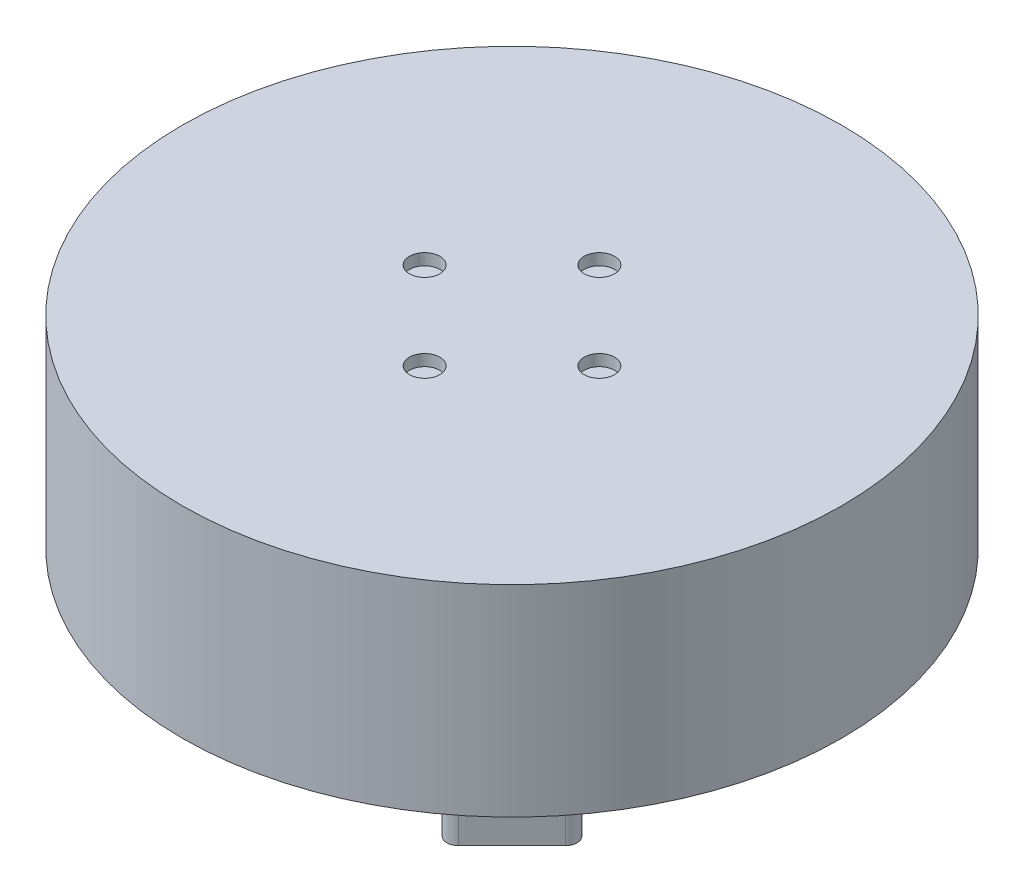
SolidWorks part; units mm, degrees
ref_plane "Front Plane" through (0, 0, 0) normal (0, 0, 1) x (1, 0, 0)
ref_plane "Top Plane" through (0, 0, 0) normal (0, 1, 0) x (1, 0, 0)
ref_plane "Right Plane" through (0, 0, 0) normal (1, 0, 0) x (0, 0, -1)
sketch "Sketch1" plane through (0, 0, 0) normal (0, 1, 0) x (1, 0, 0)
  circle A0 centre (0, 0) radius 43.4
  dimension "D1" = 86.8
extrude "Boss-Extrude1" add sketch "Sketch1" along normal blind 26.5
sketch "Sketch2" plane through (0, 0, 0) normal (0, -1, 0) x (1, 0, 0)
  circle A0 centre (0, 0) radius 16 construction
  circle A1 centre (0, 16) radius 2
  circle A2 centre (16, 0) radius 2
  circle A3 centre (0, -16) radius 2
  circle A4 centre (-16, 0) radius 2
  point P14 (0, 0)
  dimension "D1" = 32
  dimension "D2" = 4
  dimension "D3" = 4
extrude "Cut-Extrude1" cut sketch "Sketch2" against normal blind 1.5
sketch "Sketch3" plane through (0, 0, 0) normal (0, -1, 0) x (1, 0, 0)
  line L0 (0, 0) -> (0, 16) construction
  line L1 (0, 16) -> (16, 0) construction
  line L2 (16, 0) -> (0, 0) construction
  line L3 (0, 0) -> (26.8701, 26.8701) construction
  line L4 (23.3345, 30.4056) -> (30.4056, 23.3345) construction
  line L5 (25.1023, 32.1734) -> (32.1734, 25.1023) construction
  line L6 (21.5668, 28.6378) -> (28.6378, 21.5668) construction
  line L7 (24.3952, 31.4663) -> (31.4663, 24.3952)
  line L8 (22.2739, 29.3449) -> (29.3449, 22.2739)
  arc A0 (25.1023, 32.1734) -> (21.5668, 28.6378) centre (23.3345, 30.4056) ccw construction
  arc A1 (28.6378, 21.5668) -> (32.1734, 25.1023) centre (30.4056, 23.3345) ccw construction
  arc A2 (29.3449, 22.2739) -> (31.4663, 24.3952) centre (30.4056, 23.3345) ccw
  arc A3 (24.3952, 31.4663) -> (22.2739, 29.3449) centre (23.3345, 30.4056) ccw
  point P9 (26.8701, 26.8701)
  dimension "D3" = 2.5
  dimension "D1" = 38
  dimension "D2" = 10
  dimension "D4" = 1
extrude "Boss-Extrude2" add sketch "Sketch3" along normal blind 6
sketch "Sketch4" plane through (0, 26.5, 0) normal (0, 1, 0) x (1, 0, 0)
  circle A0 centre (0, 0) radius 11.5 construction
  circle A1 centre (0, 11.5) radius 2
  circle A2 centre (11.5, 0) radius 2
  circle A3 centre (0, -11.5) radius 2
  circle A4 centre (-11.5, 0) radius 2
  point P14 (0, 0)
  dimension "D2" = 4
  dimension "D3" = 4
  dimension "D1" = 23
extrude "Cut-Extrude2" cut sketch "Sketch4" against normal blind 1.5
equation "\"Np_b\" = 48"
equation "\"module\" = 0.5"
equation "\"pressure angle\" = 20.0"
equation "\"h_a\" = 0.5"
equation "\"h_b\" = 0.625"
equation "\"clr_tip_root\" = 0.125"
equation "\"fw_p_s\" = 15.90536252346366"
equation "\"Nr_s\" = 132"
equation "\"pressure_angle\" = 20.0"
equation "\"h_f\" = 0.625"
equation "\"dp_r_s\" = 66.0"
equation "\"db_r_s\" = 62.01971297186996"
equation "\"fw_r_s\" = 14.40536252346366"
equation "\"alpha_r_s\" = 0.8539582918412449"
equation "\"beta_r_s\" = 3.071552947318853"
equation "\"bearing_ID\" = 60"
equation "\"bearing_OD\" = 78"
equation "\"bearing_height\" = 10"
equation "\"clearance_planet\" = 1.5"
equation "\"case_dist\" = 6.5"
equation "\"Motor_case_OD_max\" = 111.3"
equation "\"case_mounting_PCD\" = 103.8"
equation "\"bearing mount thickness\" = 8"
equation "\"case_mounting_hole_dia\" = 3"
equation "\"output_mounting_PCD\" = 86"
equation "\"output_mounting_hole_dia\" = 4"
equation "\"clearance_case_mount_holes_shell_thickness\" = 1"
equation "\"motor_case_OD_base\" = 101.8"
equation "\"sec_carrier_thickness\" = 5"
equation "\"sun_coupler_hub_thickness\" = 4"
equation "\"clearance_sun_coupler_sec_carrier\" = 1.5"
equation "\"clearance_motor_and_case\" = 5"
equation "\"motor_OD\" = 86.8"
equation "\"Motor_case_thickness\" = 2.5"
equation "\"Motor_case_ID\" = 96.8"
equation "\"case_mounting_hole_shift\" = 1.0"
equation "\"output_mounting_nut_wrench_size\" = 7"
equation "\"output_mounting_nut_thickness\" = 3.2"
equation "\"case_mounting_hole_allen_socket_dia\" = 5.5"
equation "\"output_mounting_nut_depth\" = 3"
equation "\"case_mounting_bolt_depth\" = 4.5"
equation "\"Ns\" = 56"
equation "\"ring_radial_thickness\" = 5"
equation "\"ring_OD\"= \"Nr_s\" * \"module\" + \"ring_radial_thickness\" * 2"
equation "\"ring_to_chamfer_clearance\" = 1.5"
equation "\"Motor_case_OD_base_to_chamfer\" = 5"
equation "\"pattern_offset_from_motor_case_OD_base\" = 3"
equation "\"pattern_bulge_dia\" = 3"
equation "\"pattern_num_bulge\" = 18"
equation "\"pattern_depth\" = 2"
equation "\"motor_height\" = 26.5"
equation "\"case_mounting_wrench_size\" = 5.5"
equation "\"case_mounting_nut_clearance\" = 2"
equation "\"base_plate_thickness\" = 4"
equation "\"case_mounting_nut_thickness\" = 2.4"
equation "\"case_mounting_surface_height\" = 4"
equation "\"motor_mount_hole_PCD\" = 32"
equation "\"motor_mount_hole_dia\" = 4"
equation "\"motor_mount_hole_num\" = 4"
equation "\"central_hole_offset_from_motor_mount_PCD\" = 5"
equation "\"wire_slot_dist_from_center\" = 38"
equation "\"wire_slot_length\" = 10"
equation "\"wire_slot_radius\" = 2.5"
equation "\"driver_upper_holes_dist_from_center\" = 29"
equation "\"driver_lower_holes_dist_from_center\" = 13"
equation "\"driver_side_holes_dist_from_center\" = 22.5"
equation "\"driver_mount_holes_dia\" = 3"
equation "\"driver_mount_inserts_OD\" = 4.8"
equation "\"driver_mount_thickness\" = 1.5"
equation "\"driver_mount_height\" = 6"
equation "\"air_flow_hole_offset\" = 3"
equation "\"num_planet\" = 4"
equation "\"planet_pin_bolt_dia\" = 5"
equation "\"planet_pin_socket_head_dia\" = 8.5"
equation "\"carrier_PCD\" = 52.0"
equation "\"planet_shaft_dia\" = 8"
equation "\"planet_shaft_step_offset\" = 1"
equation "\"carrier_trapezoidal_support_sun_offset\" = 5"
equation "\"carrier_trapezoidal_support_hole_PCD_offset_bearing_ID\" = 4"
equation "\"carrier_trapezoidal_support_hole_dia\" = 3"
equation "\"carrier_trapezoidal_support_hole_socket_head_dia\" = 5.5"
equation "\"carrier_bearing_step_width\" = 1.5"
equation "\"standard_clearance_1_5mm\" = 1.5"
equation "\"standard_fillet_1_5mm\" = 1.5"
equation "\"sun_shaft_bearing_OD\" = 16"
equation "\"sun_shaft_bearing_width\" = 5"
equation "\"standard_bearing_insertion_chamfer\" = 0.5"
equation "\"carrier_trapezoidal_support_hole_wrench_size\" = 5.5"
equation "\"planet_pin_bolt_wrench_size\" = 8"
equation "\"planet_bearing_OD\" = 12"
equation "\"planet_bearing_width\" = 3.5"
equation "\"planet_bore\" = 10"
equation "\"D1@Boss-Extrude1\"=\"motor_height\""
equation "\"D1@Sketch1\"=\"motor_OD\""
equation "\"D1@Sketch2\"=\"motor_mount_hole_PCD\""
equation "\"D2@Sketch2\"=\"motor_mount_hole_dia\""
equation "\"D3@Sketch2\"=\"motor_mount_hole_num\""
equation "\"D1@Cut-Extrude1\"=\"standard_clearance_1_5mm\""
equation "\"D1@Sketch3\"=\"wire_slot_dist_from_center\""
equation "\"D2@Sketch3\"=\"wire_slot_length\""
equation "\"D3@Sketch3\"=\"wire_slot_radius\""
equation "\"D1@Boss-Extrude2\"=\"standard_clearance_1_5mm\"*4"
equation "\"motor_output_hole_PCD\" = 23"
equation "\"motor_output_hole_dia\" = 4"
equation "\"motor_output_hole_num\" = 4"
equation "\"D1@Sketch4\"=\"motor_output_hole_PCD\""
equation "\"D2@Sketch4\"=\"motor_output_hole_dia\""
equation "\"D3@Sketch4\"=\"motor_output_hole_num\""
equation "\"D1@Cut-Extrude2\"=\"standard_clearance_1_5mm\""
equation "\"dp_s\" = 28.0"
equation "\"db_s\" = 26.311393382005434"
equation "\"fw_s_calc\" = 2.7970255760332914"
equation "\"alpha_s\" = 0.8539582918412485"
equation "\"beta_s\" = 1.5063691306032174"
equation "\"dp_p_b\" = 24.0"
equation "\"db_p_b\" = 22.552622898861802"
equation "\"alpha_p_b\" = 0.8539582918412414"
equation "\"beta_p_b\" = 2.042083416317517"
equation "\"sun_shaft_bearing_ID\" = 8"
equation "\"sun_hub_dia\" = 30.0"
equation "\"sun_central_bolt_dia\" = 5"
equation "\"sun_central_bolt_socket_head_dia\" = 8.5"
equation "\"fw_s_used\" = 33.32338113475014"
equation "\"motor_output_hole_CSK_OD\" = 8"
equation "\"motor_output_hole_CSK_head_height\" = 2.0"
equation "\"bearing_retainer_thickness\" = 2"
equation "\"Np_s\" = 28"
equation "\"fw_p_b\" = 9.918018611286483"
equation "\"dp_p_s\" = 14.0"
equation "\"db_p_s\" = 13.155696691002717"
equation "\"alpha_p_s\" = 0.8539582918412485"
equation "\"beta_p_s\" = 4.720654844888932"
equation "\"clr_tip_root_s\" = 0.125"
equation "\"Nr_b\" = 152"
equation "\"fw_r_b\" = 9.918018611286483"
equation "\"dp_r_b\" = 76.0"
equation "\"db_r_b\" = 71.41663917972905"
equation "\"alpha_r_b\" = 0.8539582918412236"
equation "\"beta_r_b\" = 2.8921271099982366"
equation "\"ring_OD_b\" = 86.0"
equation "\"small_ring_case_thickness\" = 4"
equation "\"carrier_thickness\" = 4"
equation "\"small_ring_output_wall_thickness\" = 5"
equation "\"small_ring_output_wall_to_bearing_shaft_attachement_hole_dia\" = 4"
equation "\"small_ring_output_wall_to_bearing_shaft_attachement_hole_depth\" = 6.5"
equation "\"small_ring_output_wall_to_bearing_shaft_attachement_nut_wrench\" = 7"
equation "\"small_ring_output_wall_to_bearing_shaft_attachement_nut_thickness\" = 3.2"
equation "\"small_ring_output_wall_to_bearing_shaft_attachement_hole_pcd\" = 12"
equation "\"small_ring_output_wall_to_bearing_shaft_attachement_hole_num\" = 3"
equation "\"small_ring_output_wall_to_bearing_shaft_attachement_hole_CSK_OD\" = 8"
equation "\"small_ring_output_wall_to_bearing_shaft_attachement_hole_CSK_head_height\" = 2.0"
equation "\"carrier_small_ring_inner_bearing_ID\" = 20"
equation "\"carrier_small_ring_inner_bearing_OD\" = 32"
equation "\"carrier_small_ring_inner_bearing_height\" = 7"
equation "\"carrier_small_ring_inner_bearing_flap\" = 2"
equation "\"gear_casing_big_ring_to_bearing_dist\" = 24.90536252346366"
equation "\"gear_casing_thickness\" = 4"
